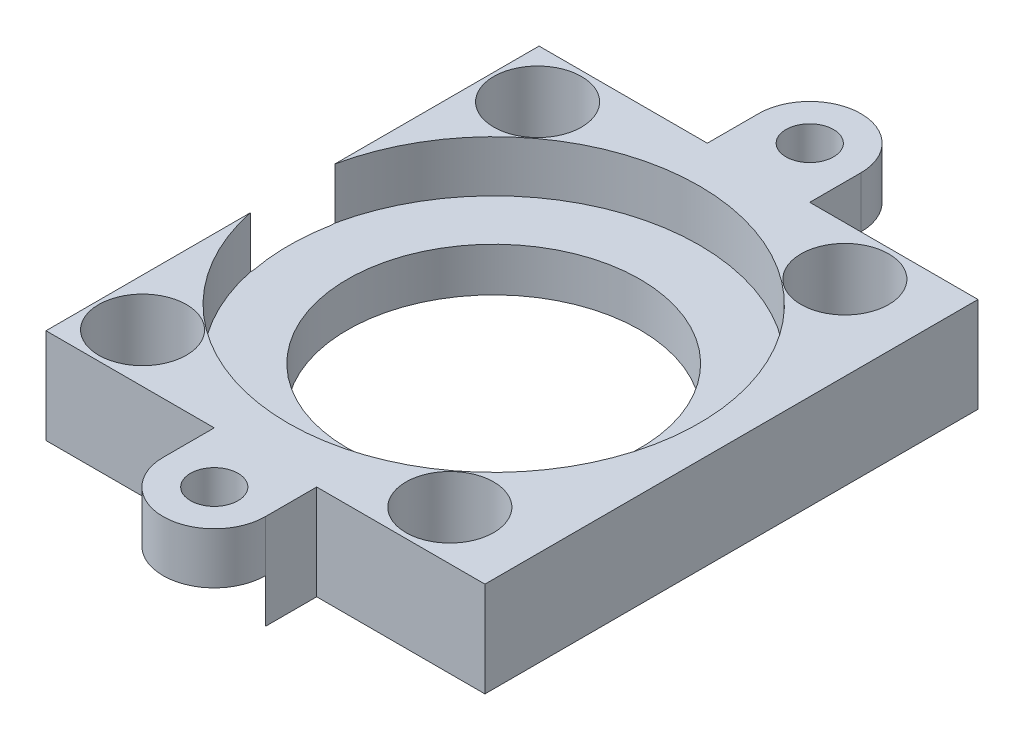
SolidWorks part; units mm, degrees
ref_plane "Front Plane" through (0, 0, 0) normal (0, 0, 1) x (1, 0, 0)
ref_plane "Top Plane" through (0, 0, 0) normal (0, 1, 0) x (1, 0, 0)
ref_plane "Right Plane" through (0, 0, 0) normal (1, 0, 0) x (0, 0, -1)
sketch "Sketch1" plane through (0, 0, 0) normal (0, 1, 0) x (1, 0, 0)
  line L1 (15, -16.85) -> (-15, -16.85)
  line L2 (15, -16.85) -> (15, 16.85)
  line L3 (15, 16.85) -> (-15, 16.85)
  line L4 (-15, -16.85) -> (-15, 16.85)
  line L5 (15, -16.85) -> (-15, 16.85) construction
  line L6 (15, 16.85) -> (-15, -16.85) construction
  circle A0 centre (-11.75, 13.5) radius 1.375
  circle A1 centre (-11.75, -13.5) radius 1.375
  circle A2 centre (9.25, -13.5) radius 1.4608
  circle A3 centre (9.25, 13.5) radius 1.4807
  circle A4 centre (-1.25, 0) radius 14
  point P0 (0, 0)
  dimension "D3" = 27
  dimension "D4" = 2.75
  dimension "D5" = 2.75
  dimension "D6" = 3.35
  dimension "D7" = 3.25
  dimension "D8" = 3.25
  dimension "D9" = 21
  dimension "D10" = 21
  dimension "D11" = 3.35
  dimension "D12" = 3.35
  dimension "D13" = 28
  dimension "D14" = 13.75
  dimension "D1" = 33.7
  dimension "D2" = 30
extrude "Boss-Extrude1" add sketch "Sketch1" along normal blind 15 contours A4 L4 L1 L2 L3 A3 A2 A1 A0
sketch "Sketch2" plane through (0, 15, 0) normal (0, 1, 0) x (1, 0, 0)
  circle A0 centre (-1.25, 0) radius 14
  circle A1 centre (-1.25, 0) radius 10
  dimension "D1" = 20
extrude "Boss-Extrude2" add sketch "Sketch2" against normal blind 8
sketch "Sketch3" plane through (0, 15, 0) normal (0, 1, 0) x (1, 0, 0)
  circle A0 centre (-1.25, 0) radius 14
  circle A1 centre (-1.25, 0) radius 10
extrude "Cut-Extrude1" cut sketch "Sketch3" against normal blind 3
sketch "Sketch5" plane through (0, 15, 0) normal (0, 1, 0) x (1, 0, 0)
  line L1 (15, -16.85) -> (-15, -16.85)
  line L2 (15, -16.85) -> (15, 16.85)
  line L3 (15, 16.85) -> (-15, 16.85)
  line L4 (-15, -16.85) -> (-15, 16.85)
  line L5 (15, -16.85) -> (-15, 16.85) construction
  line L6 (15, 16.85) -> (-15, -16.85) construction
  circle A0 centre (-1.25, 0) radius 14
  circle A1 centre (-11.75, 13.5) radius 1.375
  circle A2 centre (9.25, 13.5) radius 1.4807
  circle A3 centre (9.25, -13.5) radius 1.4608
  circle A4 centre (-11.75, -13.5) radius 1.375
  point P3 (0, 0)
  arc M1 (-15, 2.6339) -> (-15, -2.6339) centre (-1.25, 0) cw
  line M2 (-15, -2.6339) -> (-15, -16.85)
  line M3 (-15, -16.85) -> (15, -16.85)
  line M4 (15, -16.85) -> (15, 16.85)
  line M5 (15, 16.85) -> (-15, 16.85)
  line M6 (-15, 16.85) -> (-15, 2.6339)
  circle M7 centre (9.25, 13.5) radius 1.4807
  circle M8 centre (9.25, -13.5) radius 1.4608
  circle M9 centre (-11.75, -13.5) radius 1.375
  circle M10 centre (-11.75, 13.5) radius 1.375
extrude "Boss-Extrude3" add sketch "Sketch5" along normal blind 0.5 contours M6 M1 M2 M3 M4 M5 M7 M9 M10 M8
sketch "Sketch6" plane through (0, 0, 0) normal (0, -1, 0) x (1, 0, 0)
  line L1 (16.2077, -17.3573) -> (-16.2077, -17.3573)
  line L2 (16.2077, -17.3573) -> (16.2077, 17.3573)
  line L3 (16.2077, 17.3573) -> (-16.2077, 17.3573)
  line L4 (-16.2077, -17.3573) -> (-16.2077, 17.3573)
  line L5 (16.2077, -17.3573) -> (-16.2077, 17.3573) construction
  line L6 (16.2077, 17.3573) -> (-16.2077, -17.3573) construction
  point P0 (0, 0)
extrude "Cut-Extrude2" cut sketch "Sketch6" against normal blind 7
sketch "Sketch7" plane through (0, 7, 0) normal (0, -1, 0) x (1, 0, 0)
  line L1 (16.7176, -17.9135) -> (-16.7176, -17.9135)
  line L2 (16.7176, -17.9135) -> (16.7176, 17.9135)
  line L3 (16.7176, 17.9135) -> (-16.7176, 17.9135)
  line L4 (-16.7176, -17.9135) -> (-16.7176, 17.9135)
  line L5 (16.7176, -17.9135) -> (-16.7176, 17.9135) construction
  line L6 (16.7176, 17.9135) -> (-16.7176, -17.9135) construction
  point P0 (0, 0)
extrude "Cut-Extrude3" cut sketch "Sketch7" against normal blind 2
sketch "Sketch8" plane through (0, 9, 0) normal (0, -1, 0) x (1, 0, 0)
  line L0 (-15, 16.85) -> (15, 16.85) construction
  line L1 (-15, -16.85) -> (15, -16.85) construction
  line L3 (-3.5, 20.35) -> (3.5, 20.35)
  line L4 (-3.5, 20.35) -> (-3.5, -20.35)
  line L5 (-3.5, -20.35) -> (3.5, -20.35)
  line L6 (3.5, 20.35) -> (3.5, -20.35)
  circle A0 centre (0, 20.35) radius 1.625
  circle A1 centre (0, -20.35) radius 1.625
  circle A2 centre (0, 20.35) radius 3.5
  circle A3 centre (0, -20.35) radius 3.5
  line M7 (-15, -16.85) -> (15, -16.85)
  line M9 (15, 16.85) -> (-15, 16.85)
  dimension "D1" = 3.25
  dimension "D2" = 3.25
  dimension "D3" = 7
  dimension "D4" = 7
  dimension "D5" = 3.5
  dimension "D6" = 3.5
extrude "Boss-Extrude4" add sketch "Sketch8" against normal blind 6.5 contours A2 L6 M9 | A2 L4 M9 | A2 L3 A0 | L3 A2 A0 | A3 L6 M7 | A3 L4 M7 | L5 A3 A1 | L5 A3 A1
sketch "Sketch9" plane through (0, 9, 0) normal (0, -1, 0) x (1, 0, 0)
  circle A0 centre (0, 20.35) radius 1.625
  circle A1 centre (0, 20.35) radius 3.5
  circle A2 centre (0, -20.35) radius 1.625
  circle A3 centre (0, -20.35) radius 3.5
extrude "Cut-Extrude4" cut sketch "Sketch9" against normal blind 3
sketch "Sketch10" plane through (0, 9, 0) normal (0, -1, 0) x (1, 0, 0)
  circle A0 centre (-11.75, 13.5) radius 3
  circle A1 centre (9.25, 13.5) radius 3
  circle A2 centre (9.25, -13.5) radius 3
  circle A3 centre (-11.75, -13.5) radius 3
  dimension "D1" = 6
  dimension "D2" = 6
  dimension "D3" = 6
  dimension "D4" = 6
extrude "Cut-Extrude5" cut sketch "Sketch10" against normal blind 28
sketch "Sketch11" plane through (0, 15.5, 0) normal (0, 1, 0) x (1, 0, 0)
  circle A0 centre (-1.25, 0) radius 14.05
  dimension "D1" = 28.1
extrude "Cut-Extrude6" cut sketch "Sketch11" against normal blind 3.5
